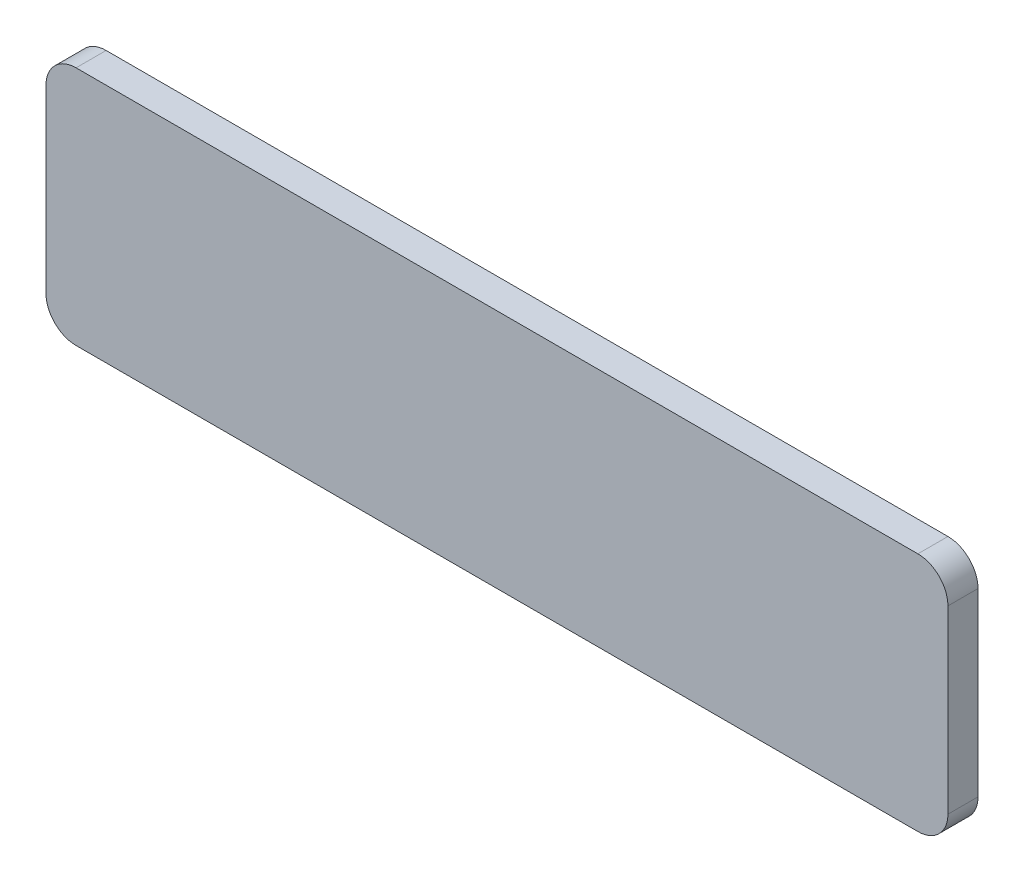
SolidWorks part; units mm, degrees
material "玻璃"
ref_plane "前视基准面" through (0, 0, 0) normal (0, 0, 1) x (1, 0, 0)
ref_plane "上视基准面" through (0, 0, 0) normal (0, 1, 0) x (1, 0, 0)
ref_plane "右视基准面" through (0, 0, 0) normal (1, 0, 0) x (0, 0, -1)
sketch "草图1" plane through (0, 0, 0) normal (0, 0, 1) x (1, 0, 0)
  line L1 (1, 0) -> (29, 0)
  line L2 (0, 1) -> (0, 7)
  line L3 (1, 8) -> (29, 8)
  line L4 (30, 1) -> (30, 7)
  arc A0 (29, 8) -> (30, 7) centre (29, 7) cw
  arc A1 (30, 1) -> (29, 0) centre (29, 1) cw
  arc A2 (0, 1) -> (1, 0) centre (1, 1) ccw
  arc A3 (0, 7) -> (1, 8) centre (1, 7) cw
  point P7 (30, 8)
  point P12 (0, 0)
  point P15 (0, 8)
  dimension "D3" = 1
  dimension "D1" = 30
  dimension "D2" = 8
extrude "凸台-拉伸1" add sketch "草图1" along normal blind 1
